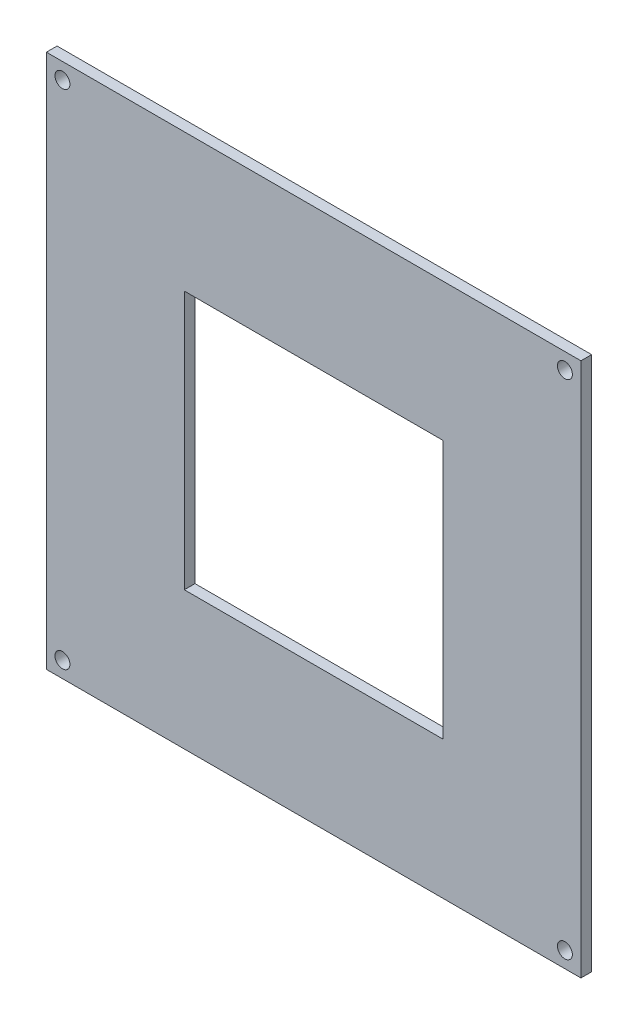
SolidWorks part; units mm, degrees
ref_plane "Plano frontal" through (0, 0, 0) normal (0, 0, 1) x (1, 0, 0)
ref_plane "Plano superior" through (0, 0, 0) normal (0, 1, 0) x (1, 0, 0)
ref_plane "Plano direito" through (0, 0, 0) normal (1, 0, 0) x (0, 0, -1)
sketch "Esboço1" plane through (0, 0, 0) normal (0, 0, 1) x (1, 0, 0)
  line L0 (-125, 125) -> (125, -125) construction
  line L1 (-125, 125) -> (125, 125)
  line L2 (-125, 125) -> (-125, -125)
  line L3 (-125, -125) -> (125, -125)
  line L4 (125, 125) -> (125, -125)
  line L5 (-125, -125) -> (125, 125) construction
  point P4 (0, 0)
  dimension "D1" = 250
  dimension "D2" = 250
extrude "Ressalto-extrusão1" add sketch "Esboço1" along normal blind 5
sketch "Esboço2" plane through (0, 0, 5) normal (0, 0, 1) x (1, 0, 0)
  line L0 (-125, 125) -> (125, -125) construction
  line L1 (-125, -125) -> (125, 125) construction
  line L2 (-110, 110) -> (-125, 110) construction
  line L3 (-125, 110) -> (-125, 125) construction
  line L4 (-125, 125) -> (-110, 125) construction
  line L5 (-110, 125) -> (-110, 110) construction
  line L6 (-125, 110) -> (-110, 125) construction
  line L7 (0, 0) -> (0, 125) construction
  line L8 (0, 0) -> (125, 0) construction
  circle A0 centre (-117.5, 117.5) radius 3.5
  circle A1 centre (117.5, 117.5) radius 3.5
  circle A2 centre (-117.5, -117.5) radius 3.5
  circle A3 centre (117.5, -117.5) radius 3.5
  point P18 (0, 0)
  dimension "D1" = 7
extrude "Corte-extrusão1" cut sketch "Esboço2" against normal through all
sketch "Esboço3" plane through (0, 0, 5) normal (0, 0, 1) x (1, 0, 0)
  line L0 (-125, 125) -> (125, -125) construction
  line L1 (-125, -125) -> (125, 125) construction
  line L2 (-60.5, 60.5) -> (60.5, -60.5) construction
  line L3 (-60.5, 60.5) -> (60.5, 60.5)
  line L4 (-60.5, 60.5) -> (-60.5, -60.5)
  line L5 (-60.5, -60.5) -> (60.5, -60.5)
  line L6 (60.5, 60.5) -> (60.5, -60.5)
  line L7 (-60.5, -60.5) -> (60.5, 60.5) construction
  point P12 (0, 0)
  point P13 (0, 0)
  point P15 (0, 0)
  dimension "D1" = 121
extrude "Corte-extrusão2" cut sketch "Esboço3" against normal through all
